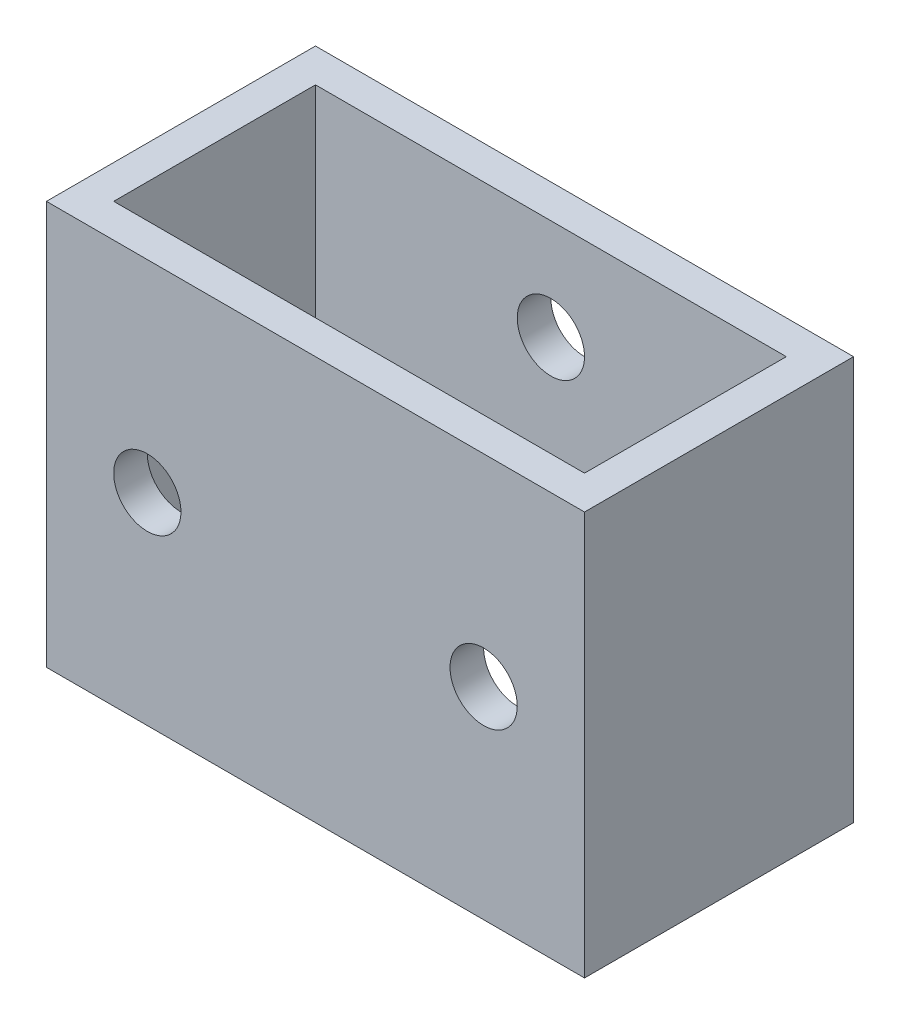
SolidWorks part; units mm, degrees
ref_plane "Front Plane" through (0, 0, 0) normal (0, 0, 1) x (1, 0, 0)
ref_plane "Top Plane" through (0, 0, 0) normal (0, 1, 0) x (1, 0, 0)
ref_plane "Right Plane" through (0, 0, 0) normal (1, 0, 0) x (0, 0, -1)
sketch "Sketch1" plane through (0, 0, 0) normal (0, 1, 0) x (1, 0, 0)
  line L1 (-25.4, 12.7) -> (25.4, 12.7)
  line L2 (-25.4, 12.7) -> (-25.4, -12.7)
  line L3 (-25.4, -12.7) -> (25.4, -12.7)
  line L4 (25.4, 12.7) -> (25.4, -12.7)
  line L5 (-25.4, 12.7) -> (25.4, -12.7) construction
  line L6 (-25.4, -12.7) -> (25.4, 12.7) construction
  line L7 (22.225, 9.525) -> (-22.225, 9.525)
  line L8 (22.225, 9.525) -> (22.225, -9.525)
  line L9 (22.225, -9.525) -> (-22.225, -9.525)
  line L10 (-22.225, 9.525) -> (-22.225, -9.525)
  line L11 (-19.05, 9.525) -> (19.05, -9.525) construction
  line L12 (-19.05, -9.525) -> (19.05, 9.525) construction
  line L13 (19.05, 9.525) -> (-19.05, -9.525) construction
  line L14 (19.05, -9.525) -> (-19.05, 9.525) construction
  line L15 (22.225, 9.525) -> (-22.225, -9.525) construction
  line L16 (22.225, -9.525) -> (-22.225, 9.525) construction
  point P0 (0, 0)
  point P6 (0, 0)
  point P11 (0, 0)
  point P16 (0, 0)
  dimension "D1" = 50.8
  dimension "D2" = 25.4
  dimension "D3" = 19.05
  dimension "D4" = 44.45
extrude "Boss-Extrude1" add sketch "Sketch1" along normal blind 38.1
sketch "Sketch2" plane through (0, 0, -12.7) normal (0, 0, -1) x (-1, 0, 0)
  line L2 (-25.4, 38.1) -> (25.4, 38.1) construction
  circle A0 centre (0, 28.575) radius 3.175
  circle A1 centre (0, 9.525) radius 3.175
  dimension "D1" = 6.35
  dimension "D2" = 19.05
  dimension "D3" = 9.525
extrude "Cut-Extrude1" cut sketch "Sketch2" against normal up to next
sketch "Sketch3" plane through (0, 0, 12.7) normal (0, 0, 1) x (1, 0, 0)
  line L0 (-25.4, 38.1) -> (25.4, 38.1) construction
  line L1 (25.4, 38.1) -> (25.4, 0) construction
  line L2 (-25.4, 38.1) -> (-25.4, 0) construction
  circle A0 centre (15.875, 19.05) radius 3.175
  circle A1 centre (-15.875, 19.05) radius 3.175
  dimension "D1" = 6.35
  dimension "D2" = 19.05
  dimension "D3" = 19.05
  dimension "D4" = 9.525
  dimension "D5" = 9.525
extrude "Cut-Extrude2" cut sketch "Sketch3" against normal up to next
